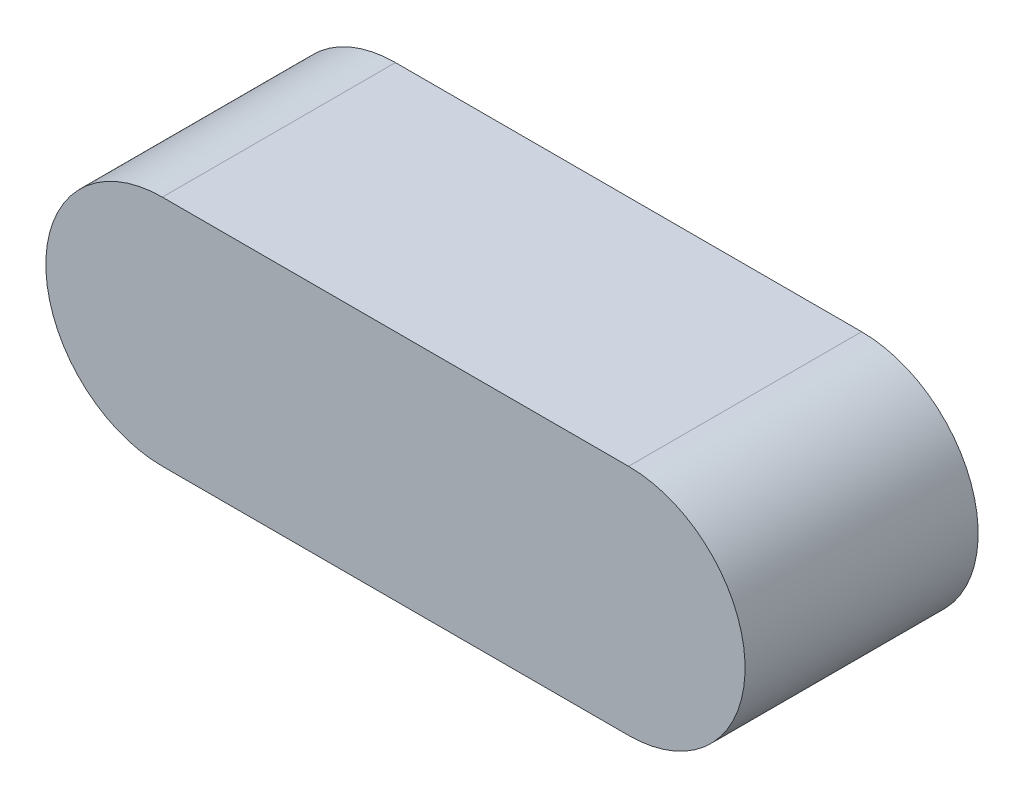
SolidWorks part; units mm, degrees
material "EN 1.5510+H Boron Steel Hardened"
ref_plane "Front Plane" through (0, 0, 0) normal (0, 0, 1) x (1, 0, 0)
ref_plane "Top Plane" through (0, 0, 0) normal (0, 1, 0) x (1, 0, 0)
ref_plane "Right Plane" through (0, 0, 0) normal (1, 0, 0) x (0, 0, -1)
sketch "Sketch1" plane through (0, 0, 0) normal (0, 0, 1) x (1, 0, 0)
  line L0 (5, -5) -> (25, -5)
  line L2 (25, -15) -> (5, -15)
  arc A1 (25, -5) -> (25, -15) centre (25, -10) cw
  arc A2 (5, -5) -> (5, -15) centre (5, -10) ccw
extrude "Boss-Extrude1" add sketch "Sketch1" along normal mid plane 10 contours L0 A1 L2 A2
